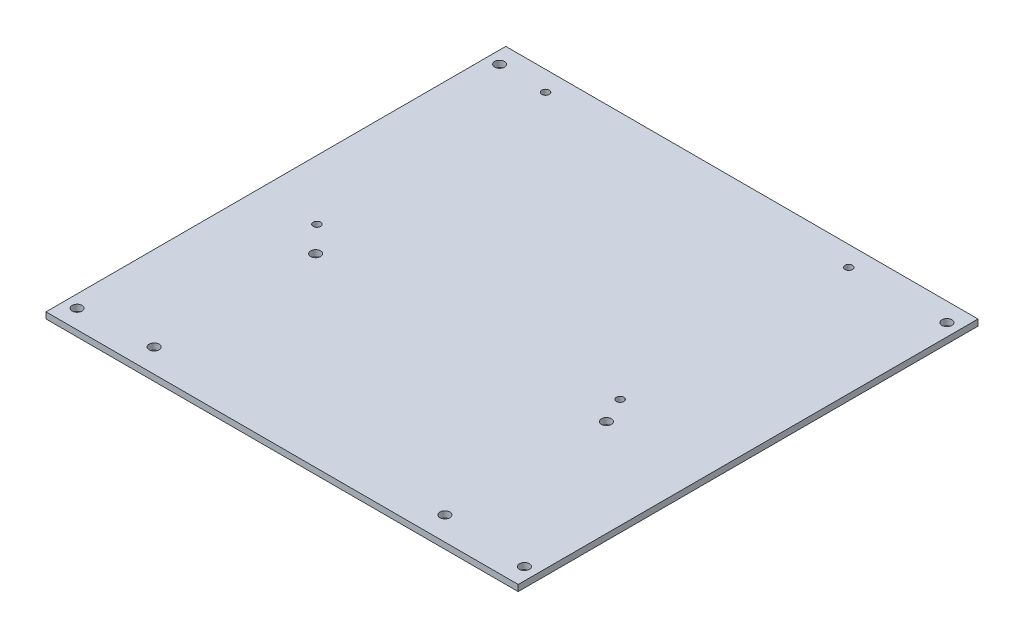
SolidWorks part; units mm, degrees
ref_plane "Front Plane" through (0, 0, 0) normal (0, 0, 1) x (1, 0, 0)
ref_plane "Top Plane" through (0, 0, 0) normal (0, 1, 0) x (1, 0, 0)
ref_plane "Right Plane" through (0, 0, 0) normal (1, 0, 0) x (0, 0, -1)
sketch "Sketch1" plane through (0, 0, 0) normal (0, 1, 0) x (1, 0, 0)
  line L1 (-95, -92.5) -> (95, -92.5)
  line L2 (-95, -92.5) -> (-95, 92.5)
  line L3 (-95, 92.5) -> (95, 92.5)
  line L4 (95, -92.5) -> (95, 92.5)
  line L5 (-95, -92.5) -> (95, 92.5) construction
  line L6 (-95, 92.5) -> (95, -92.5) construction
  point P0 (0, 0)
  dimension "D1" = 190
  dimension "D2" = 185
extrude "Boss-Extrude1" add sketch "Sketch1" along normal blind 2.5
sketch "Sketch2" plane through (0, 2.5, 0) normal (0, 1, 0) x (1, 0, 0)
  text T0 "BOTTOM" font "Century Gothic" height in points 72
extrude "Cut-Extrude1" [suppressed] cut sketch "Sketch2" against normal blind 1
sketch "Sketch3" plane through (0, 2.5, 0) normal (0, 1, 0) x (1, 0, 0)
  line L0 (95, -92.5) -> (95, 92.5) construction
  line L2 (-95, 92.5) -> (-95, -92.5) construction
  line L3 (-95, -92.5) -> (95, -92.5) construction
  line L5 (95, 92.5) -> (-95, 92.5) construction
  circle A0 centre (90, 85) radius 2
  circle A1 centre (-90, 85) radius 2
  circle A2 centre (-90, -85) radius 2
  circle A3 centre (90, -85) radius 2
  dimension "D1" = 4
  dimension "D2" = 5
  dimension "D3" = 7.5
  dimension "D6" = 5
  dimension "D7" = 7.5
  dimension "D4" = 2
  dimension "D5" = 2
extrude "Cut-Extrude2" cut sketch "Sketch3" against normal blind 10
sketch "Sketch4" plane through (0, 2.5, 0) normal (0, 1, 0) x (1, 0, 0)
  line L0 (95, -92.5) -> (95, 92.5) construction
  line L1 (-95, -92.5) -> (95, -92.5) construction
  circle A0 centre (56, -83) radius 2
  circle A1 centre (-61, -83) radius 2
  circle A2 centre (-61, -18) radius 2
  circle A3 centre (56, -18) radius 2
  dimension "D1" = 4
  dimension "D2" = 39
  dimension "D3" = 9.5
  dimension "D6" = 65
  dimension "D4" = 2
  dimension "D5" = 2
extrude "Cut-Extrude3" cut sketch "Sketch4" against normal blind 10
sketch "Sketch5" plane through (0, 2.5, 0) normal (0, 1, 0) x (1, 0, 0)
  line L0 (-95, 92.5) -> (-95, -92.5) construction
  line L1 (95, 92.5) -> (-95, 92.5) construction
  circle A0 centre (-71, 84.5) radius 1.5
  circle A1 centre (51, 84.5) radius 1.5
  circle A2 centre (51, -7.5) radius 1.5
  circle A3 centre (-71, -7.5) radius 1.5
  dimension "D1" = 3
  dimension "D2" = 24
  dimension "D3" = 8
  dimension "D4" = 2
  dimension "D5" = 2
extrude "Cut-Extrude4" cut sketch "Sketch5" against normal blind 10
